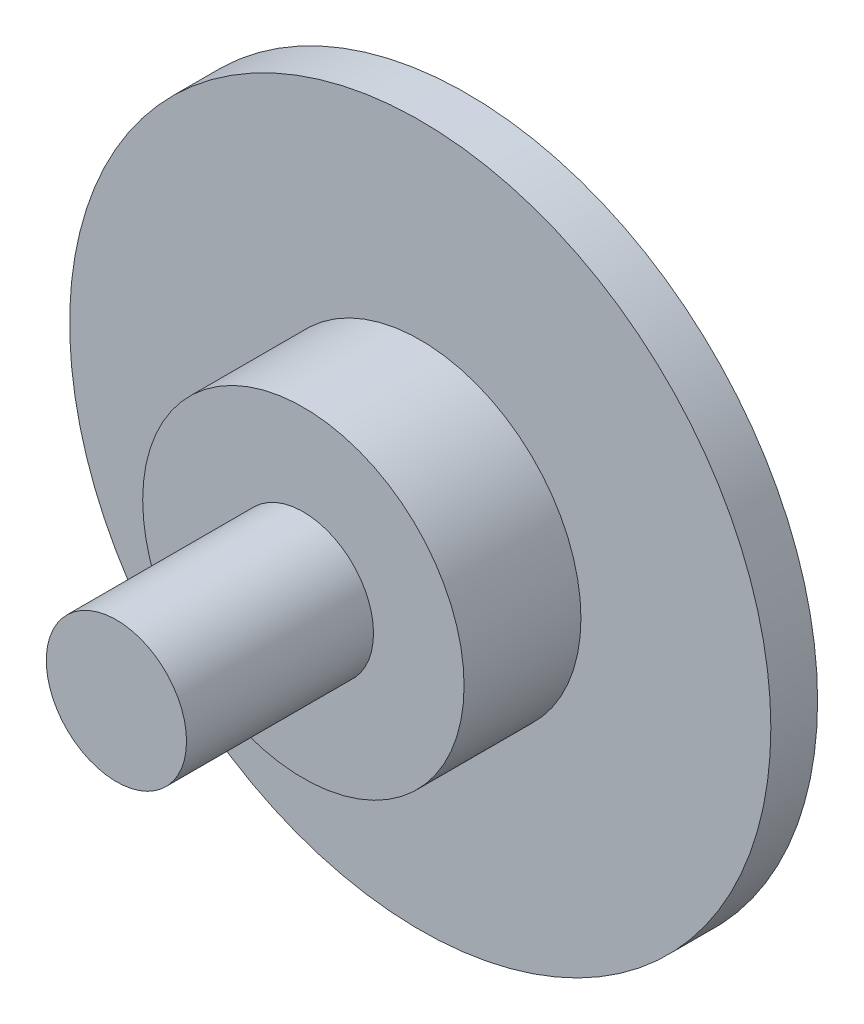
SolidWorks part; units mm, degrees
ref_plane "Front Plane" through (0, 0, 0) normal (0, 0, 1) x (1, 0, 0)
ref_plane "Top Plane" through (0, 0, 0) normal (0, 1, 0) x (1, 0, 0)
ref_plane "Right Plane" through (0, 0, 0) normal (1, 0, 0) x (0, 0, -1)
sketch "Sketch1" plane through (0, 0, 0) normal (0, 0, 1) x (1, 0, 0)
  circle A0 centre (0, 0) radius 15
  dimension "D1" = 30
extrude "Boss-Extrude1" add sketch "Sketch1" along normal blind 2
sketch "Sketch2" plane through (0, 0, 2) normal (0, 0, 1) x (1, 0, 0)
  circle A0 centre (0, 0) radius 6.875
  dimension "D1" = 13.75
extrude "Boss-Extrude2" add sketch "Sketch2" along normal blind 5
sketch "Sketch3" plane through (0, 0, 7) normal (0, 0, 1) x (1, 0, 0)
  circle A0 centre (0, 0) radius 3
  dimension "D1" = 6
extrude "Boss-Extrude3" add sketch "Sketch3" along normal blind 8
